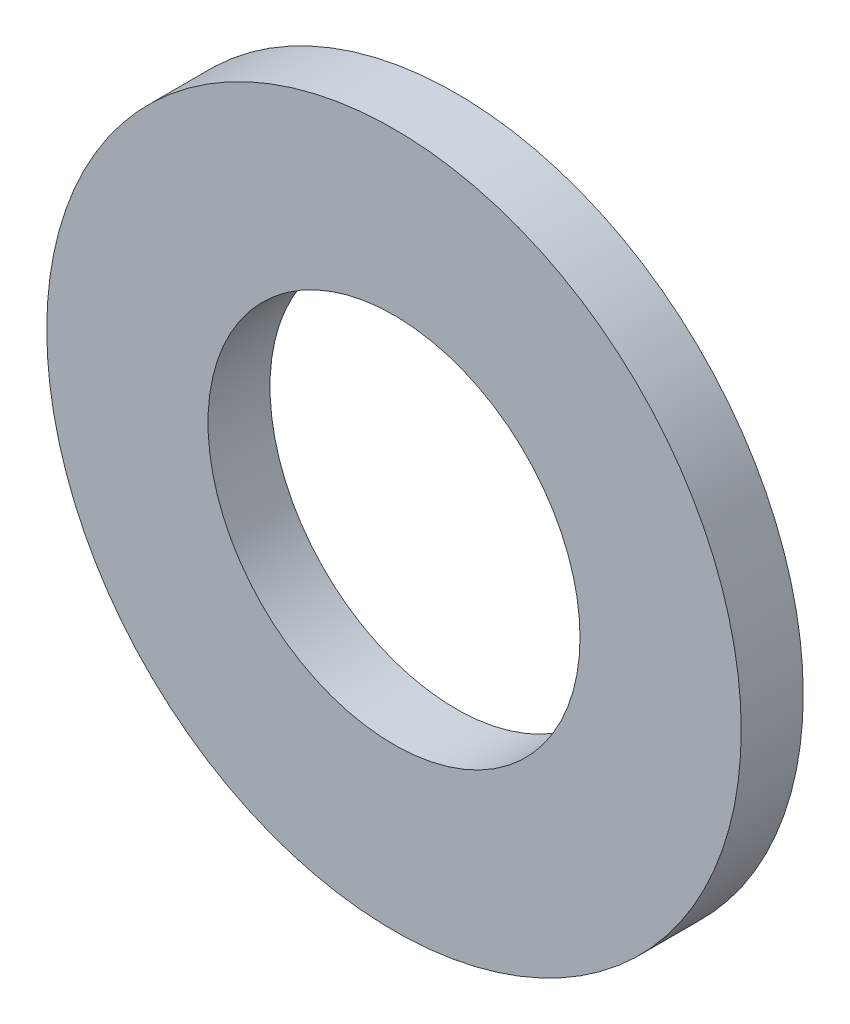
SolidWorks part; units mm, degrees
ref_plane "Front" through (0, 0, 0) normal (0, 0, 1) x (1, 0, 0)
ref_plane "Top" through (0, 0, 0) normal (0, 1, 0) x (1, 0, 0)
ref_plane "Right" through (0, 0, 0) normal (1, 0, 0) x (0, 0, -1)
sketch "Sketch1" plane through (0, 0, 0) normal (0, 0, 1) x (1, 0, 0)
  circle A0 centre (0, 0) radius 7.5
  circle A1 centre (0, 0) radius 14
  dimension "d1" = 15
  dimension "d2" = 28
extrude "Base-Extrude" add sketch "Sketch1" against normal blind 2.5
